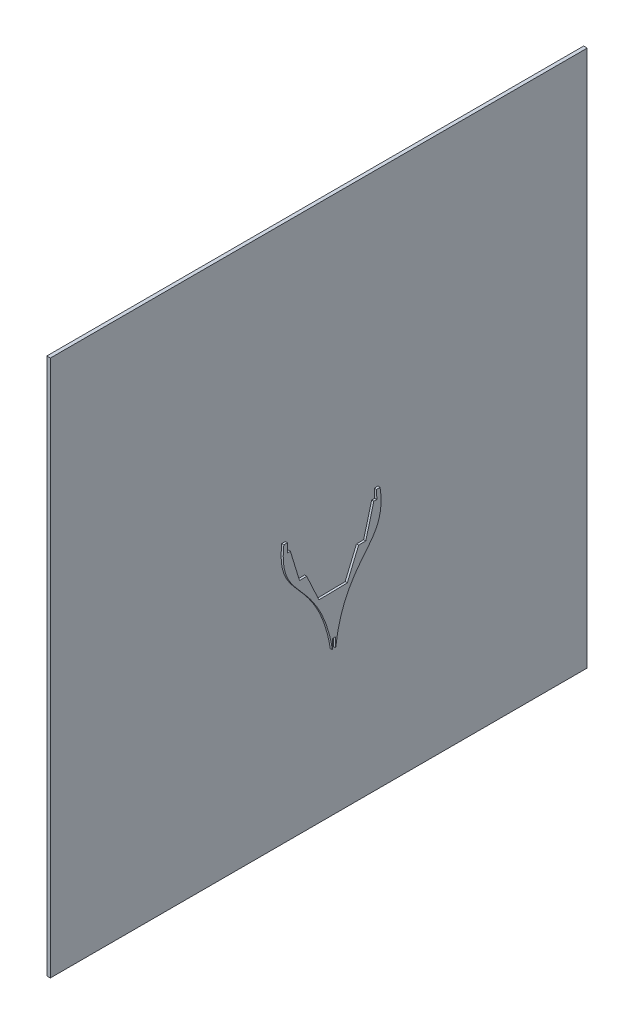
SolidWorks part; units mm, degrees
ref_plane "Plan de face" through (0, 0, 0) normal (0, 0, 1) x (1, 0, 0)
ref_plane "Plan de dessus" through (0, 0, 0) normal (0, 1, 0) x (1, 0, 0)
ref_plane "Plan de droite" through (0, 0, 0) normal (1, 0, 0) x (0, 0, -1)
sketch "Esquisse1" plane through (0, 0, 0) normal (0, 0, 1) x (1, 0, 0)
  point P0 (-20, 0)
  dimension "D1" = 20
sketch3d "Esquisse3D1"
  line L1 (-20, 1121.2893, 777.275) -> (-20, 1121.2893, -722.725)
  line L2 (-20, 1121.2893, 777.275) -> (-20, -378.7107, 777.275)
  line L3 (-20, -378.7107, 777.275) -> (-20, -378.7107, -722.725)
  line L4 (-20, 1121.2893, -722.725) -> (-20, -378.7107, -722.725)
  dimension "D1" = 1500
  dimension "D2" = 1500
extrude "Boss.-Extru.2" add sketch "Esquisse3D1" along direction (1, 0, 0) on the side of the normal blind 10 contours L2 L1 L4 L3
sketch "Esquisse4" plane through (-10, 0, 0) normal (1, 0, 0) x (0, 0, -1)
  line L0 (0, 0) -> (-7.701, 425.1082) construction
  line L1 (169.3944, 339.9131) -> (-188.5193, 333.4294) construction
  line L2 (-187.2006, 249.23) -> (169.0622, 255.6839) construction
  line L3 (-144.268, 175.2448) -> (126.4811, 180.1495) construction
sketch "Esquisse5" plane through (0, 0, 0) normal (1, 0, 0) x (0, 0, -1)
  line L0 (-7.701, 425.1082) -> (0, 0) construction
  line L2 (0, 0) -> (3.955, 18.2202) construction
  line L3 (3.955, 18.2202) -> (2.4421, 267.2667) construction
  line L4 (2.4421, 267.2667) -> (154.2161, 190.0835) construction
  line L5 (154.2161, 190.0835) -> (127.9036, 364.0218) construction
  line L8 (127.9036, 364.0218) -> (117.9036, 363.8406)
  line L9 (117.9036, 363.8406) -> (118.9371, 338.9991)
  line L10 (169.3944, 339.9131) -> (-188.5193, 333.4294) construction
  line L11 (118.9371, 338.9991) -> (110.5492, 338.8471)
  line L12 (110.5492, 338.8471) -> (87.9969, 254.2153)
  line L13 (-187.2006, 249.23) -> (169.0622, 255.6839) construction
  line L14 (87.9969, 254.2153) -> (68.0137, 253.8533)
  line L15 (68.0137, 253.8533) -> (36.3944, 178.5175)
  line L16 (-144.268, 175.2448) -> (126.4811, 180.1495) construction
  line L17 (36.3944, 178.5175) -> (-42.8362, 177.0822)
  line L18 (0, 0) -> (-4.6123, 18.065) construction
  line L19 (-4.6123, 18.065) -> (-12.1205, 267.0029) construction
  line L20 (-12.1205, 267.0029) -> (-160.9995, 184.3732) construction
  line L21 (-160.9995, 184.3732) -> (-141.0042, 359.1504) construction
  line L22 (-77.1633, 251.2234) -> (-42.8362, 177.0822)
  line L23 (-97.1466, 250.8614) -> (-77.1633, 251.2234)
  line L24 (-122.7494, 334.6208) -> (-97.1466, 250.8614)
  line L25 (-131.1373, 334.4689) -> (-122.7494, 334.6208)
  line L26 (-131.0042, 359.3316) -> (-131.1373, 334.4689)
  line L27 (-141.0042, 359.1504) -> (-131.0042, 359.3316)
  spline S0 degree 4 poles (0, 0) (3.955, 18.2202) (2.4421, 267.2667) (154.2161, 190.0835) (127.9036, 364.0218) knots 0 0 0 0 0 1 1 1 1 1
  spline S1 degree 4 poles (0, 0) (-4.6123, 18.065) (-12.1205, 267.0029) (-160.9995, 184.3732) (-141.0042, 359.1504) knots 0 0 0 0 0 1 1 1 1 1
  point P30 (-3.2209, 177.7999)
  dimension "D1" = 10
extrude "Boss.-Extru.3" add sketch "Esquisse5" along normal blind 6 separate body
sketch "Esquisse6" plane through (6, 0, 0) normal (1, 0, 0) x (0, 0, -1)
  line L0 (-5.1786, 37.3765) -> (-5.6677, 64.3765)
  line L1 (-5.6677, 64.3765) -> (3.3323, 64.5395)
  line L2 (3.3323, 64.5395) -> (3.8214, 37.5395)
  line L3 (3.8214, 37.5395) -> (117.0633, -47.527)
  line L4 (117.0633, -47.527) -> (-85.2277, -65.22)
  line L5 (-85.2277, -65.22) -> (-5.1786, 37.3765)
  line L6 (-5.1786, 37.3765) -> (3.8214, 37.5395) construction
  line L7 (-144.268, 175.2448) -> (126.4811, 180.1495) construction
  spline S0 degree 4 poles (-141.0042, 359.1504) (-160.9995, 184.3732) (-12.1205, 267.0029) (-4.6123, 18.065) (0, 0) knots 0 0 0 0 0 1 1 1 1 1 construction
  spline S1 degree 4 poles (0, 0) (3.955, 18.2202) (2.4421, 267.2667) (154.2161, 190.0835) (127.9036, 364.0218) knots 0 0 0 0 0 1 1 1 1 1 construction
  dimension "D1" = 9
  dimension "D2" = 27
extrude "Enlèv. mat.-Extru.1" cut sketch "Esquisse6" against normal blind 6
